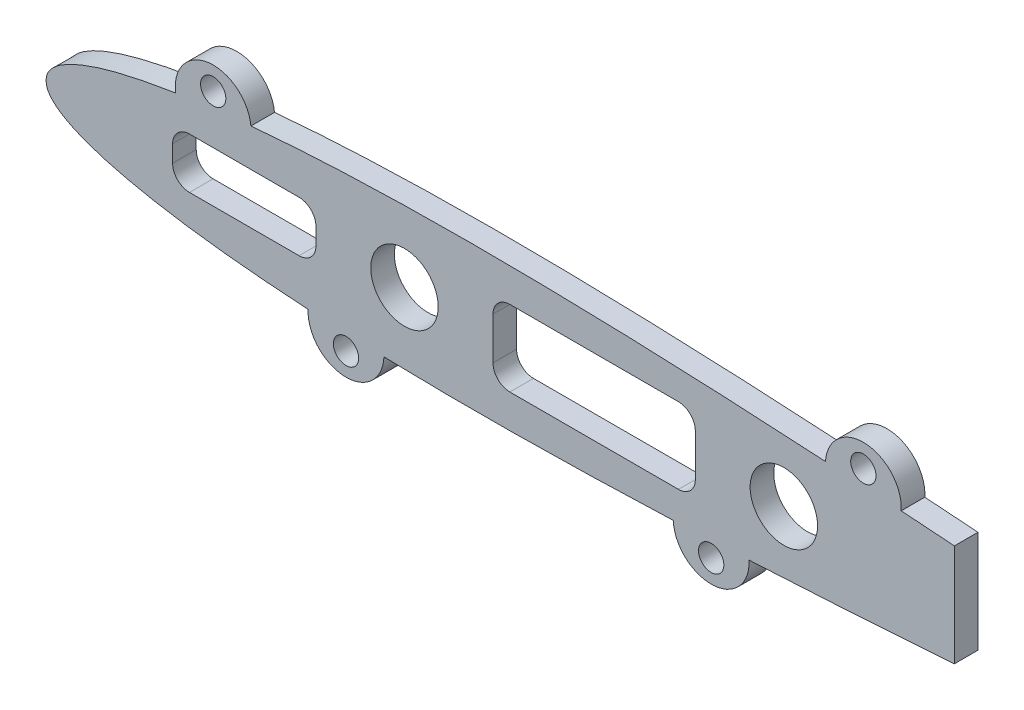
SolidWorks part; units mm, degrees
material "Фанера"
ref_plane "Front Plane" through (0, 0, 0) normal (0, 0, 1) x (1, 0, 0)
ref_plane "Top Plane" through (0, 0, 0) normal (0, 1, 0) x (1, 0, 0)
ref_plane "Right Plane" through (0, 0, 0) normal (1, 0, 0) x (0, 0, -1)
curve "Кривая1"
  spline degree 3 poles (110, 0, 0) (110.0276, -0.2367, 0) (110.0855, -0.7342, 0) (110.5302, -1.4271, 0) (111.1963, -2.0786, 0) (112.1098, -2.7013, 0) (113.2568, -3.2993, 0) (114.6379, -3.8731, 0) (116.2477, -4.4214, 0) (118.0813, -4.9426, 0) (120.1331, -5.4348, 0) (122.3972, -5.8961, 0) (124.8672, -6.3247, 0) (127.537, -6.7187, 0) (130.3997, -7.0764, 0) (133.4488, -7.3965, 0) (136.6771, -7.6776, 0) (140.0777, -7.9187, 0) (143.6433, -8.119, 0) (147.3662, -8.278, 0) (151.2389, -8.3955, 0) (155.2534, -8.4715, 0) (159.4016, -8.5065, 0) (163.6751, -8.501, 0) (168.0653, -8.456, 0) (172.5632, -8.3725, 0) (177.1595, -8.252, 0) (181.8446, -8.096, 0) (186.6087, -7.9062, 0) (191.4413, -7.6846, 0) (196.3316, -7.4331, 0) (201.2684, -7.1538, 0) (206.2396, -6.8489, 0) (211.233, -6.5205, 0) (216.2352, -6.1709, 0) (221.2323, -5.8022, 0) (226.2093, -5.417, 0) (231.1504, -5.0174, 0) (236.0382, -4.6058, 0) (240.8542, -4.1849, 0) (245.5777, -3.7574, 0) (250.1862, -3.3262, 0) (254.6542, -2.8948, 0) (258.9526, -2.4672, 0) (263.0477, -2.0479, 0) (266.899, -1.6426, 0) (270.4558, -1.2586, 0) (273.6512, -0.9053, 0) (276.3854, -0.5964, 0) (278.4526, -0.359, 0) (279.592, -0.2261, 0) (280, -0.1785, 0) knots 0 0 0 0 0.004099 0.008615 0.013935 0.020278 0.027753 0.03641 0.046266 0.05732 0.069559 0.082963 0.097507 0.113164 0.129903 0.14769 0.166492 0.186272 0.206992 0.228612 0.251092 0.274389 0.298458 0.323254 0.348728 0.37483 0.401509 0.42871 0.456376 0.484448 0.512864 0.541558 0.570462 0.599504 0.628607 0.65769 0.686667 0.715445 0.743924 0.771995 0.79954 0.826428 0.852512 0.877624 0.901571 0.924121 0.944989 0.963804 0.980044 0.992855 1 1 1 1
curve "Кривая2"
  spline degree 3 poles (280, 0.1785, 0) (279.592, 0.2261, 0) (278.4526, 0.359, 0) (276.3854, 0.5964, 0) (273.6512, 0.9053, 0) (270.4558, 1.2586, 0) (266.899, 1.6426, 0) (263.0477, 2.0479, 0) (258.9526, 2.4672, 0) (254.6542, 2.8948, 0) (250.1862, 3.3262, 0) (245.5777, 3.7574, 0) (240.8542, 4.1849, 0) (236.0382, 4.6058, 0) (231.1504, 5.0174, 0) (226.2093, 5.417, 0) (221.2323, 5.8022, 0) (216.2352, 6.1709, 0) (211.233, 6.5205, 0) (206.2396, 6.8489, 0) (201.2684, 7.1538, 0) (196.3316, 7.4331, 0) (191.4413, 7.6846, 0) (186.6087, 7.9062, 0) (181.8446, 8.096, 0) (177.1595, 8.252, 0) (172.5632, 8.3725, 0) (168.0653, 8.456, 0) (163.6751, 8.501, 0) (159.4016, 8.5065, 0) (155.2534, 8.4715, 0) (151.2389, 8.3955, 0) (147.3662, 8.278, 0) (143.6433, 8.119, 0) (140.0777, 7.9187, 0) (136.6771, 7.6776, 0) (133.4488, 7.3965, 0) (130.3997, 7.0764, 0) (127.537, 6.7187, 0) (124.8672, 6.3247, 0) (122.3972, 5.8961, 0) (120.1331, 5.4348, 0) (118.0813, 4.9426, 0) (116.2477, 4.4214, 0) (114.6379, 3.8731, 0) (113.2568, 3.2993, 0) (112.1098, 2.7013, 0) (111.1963, 2.0786, 0) (110.5302, 1.4271, 0) (110.0855, 0.7342, 0) (110.0276, 0.2367, 0) (110, 0, 0) knots 0 0 0 0 0.007145 0.019956 0.036196 0.055011 0.075879 0.098429 0.122376 0.147488 0.173572 0.20046 0.228005 0.256076 0.284555 0.313333 0.34231 0.371393 0.400496 0.429538 0.458442 0.487136 0.515552 0.543624 0.57129 0.598491 0.62517 0.651272 0.676746 0.701542 0.725611 0.748908 0.771388 0.793008 0.813728 0.833508 0.85231 0.870097 0.886836 0.902493 0.917037 0.930441 0.94268 0.953734 0.96359 0.972247 0.979722 0.986065 0.991385 0.995901 1 1 1 1
sketch "Эскиз1" plane through (0, 0, 0) normal (0, 0, 1) x (1, 0, 0)
  line L0 (105.1708, 0) -> (280.7263, 0) construction
  line L1 (280.0739, 0) -> (280.0739, 24.3846) construction
  line L2 (110, -5.3315) -> (110, 17.5304) construction
  line L3 (152.5185, 18.8331) -> (152.5185, -21.3473) construction
  line L4 (223.3826, 13.2402) -> (223.3826, -18.4275) construction
  line L5 (217.7476, 6.0581) -> (217.7476, -6.0581)
  line L6 (127.0185, -3) -> (140.0185, -3)
  line L7 (125.0185, -1) -> (125.0185, 1)
  line L8 (127.0185, 3) -> (140.0185, 3)
  line L9 (142.0185, -1) -> (142.0185, 1)
  line L10 (125.0185, -3) -> (142.0185, 3) construction
  line L11 (125.0185, 3) -> (142.0185, -3) construction
  line L12 (165.0185, -4.5) -> (185.0185, -4.5)
  line L13 (163.0185, -2.5) -> (163.0185, 2.5)
  line L14 (165.0185, 4.5) -> (185.0185, 4.5)
  line L15 (187.0185, -2.5) -> (187.0185, 2.5)
  line L16 (163.0185, -4.5) -> (187.0185, 4.5) construction
  line L17 (163.0185, 4.5) -> (187.0185, -4.5) construction
  arc A0 (280, 0.1785) -> (280, -0.1785) centre (279.8215, 0) cw
  circle A1 centre (152.5185, 0) radius 4
  circle A2 centre (197.5185, 0) radius 4
  arc A3 (185.0185, 4.5) -> (187.0185, 2.5) centre (185.0185, 2.5) cw
  arc A4 (185.0185, -4.5) -> (187.0185, -2.5) centre (185.0185, -2.5) ccw
  arc A5 (165.0185, -4.5) -> (163.0185, -2.5) centre (165.0185, -2.5) cw
  arc A6 (163.0185, 2.5) -> (165.0185, 4.5) centre (165.0185, 2.5) cw
  arc A7 (125.0185, 1) -> (127.0185, 3) centre (127.0185, 1) cw
  arc A8 (127.0185, -3) -> (125.0185, -1) centre (127.0185, -1) cw
  arc A9 (140.0185, -3) -> (142.0185, -1) centre (140.0185, -1) ccw
  arc A10 (140.0185, 3) -> (142.0185, 1) centre (140.0185, 1) cw
  arc A11 (223.3826, 5.635) -> (223.3826, -5.635) centre (223.3826, 0) ccw
  circle A12 centre (223.3826, 0) radius 1
  arc A13 (134.3056, 7.4673) -> (125.371, 6.3931) centre (129.8299, 7) ccw
  arc A14 (141.0932, -7.9724) -> (150.0847, -8.3577) centre (145.5874, -8.2) ccw
  arc A15 (211.4375, 6.5031) -> (202.4559, 7.0792) centre (206.9473, 6.8) ccw
  arc A16 (184.4033, -7.9928) -> (193.3939, -7.5829) centre (188.8991, -7.8) ccw
  circle A17 centre (129.8299, 8.8) radius 1.5
  circle A18 centre (145.5874, -10) radius 1.5
  circle A19 centre (188.8991, -9.6) radius 1.5
  circle A20 centre (206.9473, 8.6) radius 1.5
  spline S0 degree 3 poles (110, 0) (110.0276, -0.2367) (110.0855, -0.7342) (110.5302, -1.4271) (111.1963, -2.0786) (112.1098, -2.7013) (113.2568, -3.2993) (114.6379, -3.8731) (116.2477, -4.4214) (118.0813, -4.9426) (120.1331, -5.4348) (122.3972, -5.8961) (124.8672, -6.3247) (127.537, -6.7187) (130.3997, -7.0764) (133.4488, -7.3965) (136.6771, -7.6776) (140.0777, -7.9187) (143.6433, -8.119) (147.3662, -8.278) (151.2389, -8.3955) (155.2534, -8.4715) (159.4016, -8.5065) (163.6751, -8.501) (168.0653, -8.456) (172.5632, -8.3725) (177.1595, -8.252) (181.8446, -8.096) (186.6087, -7.9062) (191.4413, -7.6846) (196.3316, -7.4331) (201.2684, -7.1538) (206.2396, -6.8489) (211.233, -6.5205) (216.2352, -6.1709) (221.2323, -5.8022) (226.2093, -5.417) (231.1504, -5.0174) (236.0382, -4.6058) (240.8542, -4.1849) (247.0711, -3.6222) (253.1161, -3.0479) (258.9526, -2.4672) (263.0477, -2.0479) (266.899, -1.6426) (270.4558, -1.2586) (273.6512, -0.9053) (276.3854, -0.5964) (278.4526, -0.359) (279.592, -0.2261) (280, -0.1785) knots 0 0 0 0 0.004099 0.008615 0.013935 0.020278 0.027753 0.03641 0.046266 0.05732 0.069559 0.082963 0.097507 0.113164 0.129903 0.14769 0.166492 0.186272 0.206992 0.228612 0.251092 0.274389 0.298458 0.323254 0.348728 0.37483 0.401509 0.42871 0.456376 0.484448 0.512864 0.541558 0.570462 0.599504 0.628607 0.65769 0.686667 0.715445 0.743924 0.771995 0.79954 0.852512 0.877624 0.901571 0.924121 0.944989 0.963804 0.980044 0.992855 1 1 1 1 construction
  spline S1 degree 3 poles (280, 0.1785) (279.592, 0.2261) (278.4526, 0.359) (276.3854, 0.5964) (273.6512, 0.9053) (270.4558, 1.2586) (266.899, 1.6426) (263.0477, 2.0479) (258.9526, 2.4672) (253.1161, 3.0479) (247.0711, 3.6222) (240.8542, 4.1849) (236.0382, 4.6058) (231.1504, 5.0174) (226.2093, 5.417) (221.2323, 5.8022) (216.2352, 6.1709) (211.233, 6.5205) (206.2396, 6.8489) (201.2684, 7.1538) (196.3316, 7.4331) (191.4413, 7.6846) (186.6087, 7.9062) (181.8446, 8.096) (177.1595, 8.252) (172.5632, 8.3725) (168.0653, 8.456) (163.6751, 8.501) (159.4016, 8.5065) (155.2534, 8.4715) (151.2389, 8.3955) (147.3662, 8.278) (143.6433, 8.119) (140.0777, 7.9187) (136.6771, 7.6776) (133.4488, 7.3965) (130.3997, 7.0764) (127.537, 6.7187) (124.8672, 6.3247) (122.3972, 5.8961) (120.1331, 5.4348) (118.0813, 4.9426) (116.2477, 4.4214) (114.6379, 3.8731) (113.2568, 3.2993) (112.1098, 2.7013) (111.1963, 2.0786) (110.5302, 1.4271) (110.0855, 0.7342) (110.0276, 0.2367) (110, 0) knots 0 0 0 0 0.007145 0.019956 0.036196 0.055011 0.075879 0.098429 0.122376 0.147488 0.20046 0.228005 0.256076 0.284555 0.313333 0.34231 0.371393 0.400496 0.429538 0.458442 0.487136 0.515552 0.543624 0.57129 0.598491 0.62517 0.651272 0.676746 0.701542 0.725611 0.748908 0.771388 0.793008 0.813728 0.833508 0.85231 0.870097 0.886836 0.902493 0.917037 0.930441 0.94268 0.953734 0.96359 0.972247 0.979722 0.986065 0.991385 0.995901 1 1 1 1 construction
  spline S2 degree 3 poles (110, 0) (110.0276, -0.2367) (110.0855, -0.7342) (110.5302, -1.4271) (111.1963, -2.0786) (112.1098, -2.7013) (113.2568, -3.2993) (114.6379, -3.8731) (116.2477, -4.4214) (118.0813, -4.9426) (120.1331, -5.4348) (122.3972, -5.8961) (124.8672, -6.3247) (127.537, -6.7187) (130.3997, -7.0764) (133.4488, -7.3965) (136.6771, -7.6776) (139.2456, -7.8597) (140.7369, -7.9513) (141.0932, -7.9724) knots 0 0 0 0 0.004099 0.008615 0.013935 0.020278 0.027753 0.03641 0.046266 0.05732 0.069559 0.082963 0.097507 0.113164 0.129903 0.14769 0.166492 0.186272 0.192481 0.192481 0.192481 0.192481
  spline S3 degree 3 poles (280, 0.1785) (279.592, 0.2261) (278.4526, 0.359) (276.3854, 0.5964) (273.6512, 0.9053) (270.4558, 1.2586) (266.899, 1.6426) (263.0477, 2.0479) (258.9526, 2.4672) (253.1161, 3.0479) (247.0711, 3.6222) (240.8542, 4.1849) (236.0382, 4.6058) (231.1504, 5.0174) (226.2093, 5.417) (221.2323, 5.8022) (216.3046, 6.1657) (213.0372, 6.3944) (211.4375, 6.5031) knots 0 0 0 0 0.007145 0.019956 0.036196 0.055011 0.075879 0.098429 0.122376 0.147488 0.20046 0.228005 0.256076 0.284555 0.313333 0.34231 0.371393 0.399286 0.399286 0.399286 0.399286
  spline S4 degree 3 poles (150.0847, -8.3577) (150.4538, -8.368) (152.1618, -8.413) (155.2534, -8.4715) (159.4016, -8.5065) (163.6751, -8.501) (168.0653, -8.456) (172.5632, -8.3725) (177.1595, -8.252) (181.1171, -8.1202) (183.5415, -8.0273) (184.4033, -7.9928) knots 0.244668 0.244668 0.244668 0.244668 0.251092 0.274389 0.298458 0.323254 0.348728 0.37483 0.401509 0.42871 0.443713 0.443713 0.443713 0.443713
  spline S5 degree 3 poles (125.371, 6.3931) (125.1826, 6.3638) (124.1683, 6.2034) (122.3972, 5.8961) (120.1331, 5.4348) (118.0813, 4.9426) (116.2477, 4.4214) (114.6379, 3.8731) (113.2568, 3.2993) (112.1098, 2.7013) (111.1963, 2.0786) (110.5302, 1.4271) (110.0855, 0.7342) (110.0276, 0.2367) (110, 0) knots 0.899175 0.899175 0.899175 0.899175 0.902493 0.917037 0.930441 0.94268 0.953734 0.96359 0.972247 0.979722 0.986065 0.991385 0.995901 1 1 1 1
  spline S6 degree 3 poles (202.4559, 7.0792) (202.056, 7.1032) (200.0095, 7.225) (196.3316, 7.4331) (191.4413, 7.6846) (186.6087, 7.9062) (181.8446, 8.096) (177.1595, 8.252) (172.5632, 8.3725) (168.0653, 8.456) (163.6751, 8.501) (159.4016, 8.5065) (155.2534, 8.4715) (151.2389, 8.3955) (147.3662, 8.278) (143.6433, 8.119) (140.0777, 7.9187) (136.9824, 7.6992) (135.0773, 7.5376) (134.3056, 7.4673) knots 0.451472 0.451472 0.451472 0.451472 0.458442 0.487136 0.515552 0.543624 0.57129 0.598491 0.62517 0.651272 0.676746 0.701542 0.725611 0.748908 0.771388 0.793008 0.813728 0.833508 0.846987 0.846987 0.846987 0.846987
  spline S7 degree 3 poles (193.3939, -7.5829) (194.3678, -7.5334) (196.9889, -7.3959) (201.2684, -7.1538) (206.2396, -6.8489) (211.233, -6.5205) (216.2352, -6.1709) (221.2323, -5.8022) (226.2093, -5.417) (231.1504, -5.0174) (236.0382, -4.6058) (240.8542, -4.1849) (247.0711, -3.6222) (253.1161, -3.0479) (258.9526, -2.4672) (263.0477, -2.0479) (266.899, -1.6426) (270.4558, -1.2586) (273.6512, -0.9053) (276.3854, -0.5964) (278.4526, -0.359) (279.592, -0.2261) (280, -0.1785) knots 0.4959 0.4959 0.4959 0.4959 0.512864 0.541558 0.570462 0.599504 0.628607 0.65769 0.686667 0.715445 0.743924 0.771995 0.79954 0.852512 0.877624 0.901571 0.924121 0.944989 0.963804 0.980044 0.992855 1 1 1 1
  point P19 (175.0185, 0)
  point P22 (133.5185, 0)
  point P31 (223.3826, -5.635)
  point P54 (223.3826, 5.635)
  point P55 (223.3826, -5.635)
  point P56 (223.3826, 5.635)
  point P83 (188.8991, -9.6)
  point P84 (206.9473, 8.5569)
  point P85 (199.6448, -13.452)
  point P86 (166.5843, 16.6161)
  dimension "D1" = 0.2524
  dimension "D3" = 8
  dimension "D13" = 2
  dimension "D14" = 5.635
  dimension "D15" = 2
  dimension "D16" = 9
  dimension "D21" = 3
  dimension "D2" = 170.0739
  dimension "D4" = 42.5185
  dimension "D5" = 56.6913
  dimension "D6" = 45
  dimension "D7" = 6
  dimension "D8" = 17
  dimension "D9" = 19
  dimension "D10" = 22.5
  dimension "D11" = 9
  dimension "D12" = 24
  dimension "D17" = 7
  dimension "D18" = 8.2
  dimension "D19" = 7.8
  dimension "D20" = 6.8
  dimension "D22" = 1.8
  dimension "D23" = 1.8
  dimension "D24" = 1.8
  dimension "D25" = 1.8
extrude "Бобышка-Вытянуть1" add sketch "Эскиз1" along normal mid plane 2.8 contours L5 S3 S2 L8 A10 L9 A9 L6 A8 L7 A7 L13 A6 L14 A3 L15 A4 L12 A5 A1 A2
equation "\"D4@Эскиз1\"=\"D2@Эскиз1\"/4"
equation "\"D5@Эскиз1\"=\"D2@Эскиз1\"/3"
equation "\"D10@Эскиз1\"=\"D6@Эскиз1\"/2"
